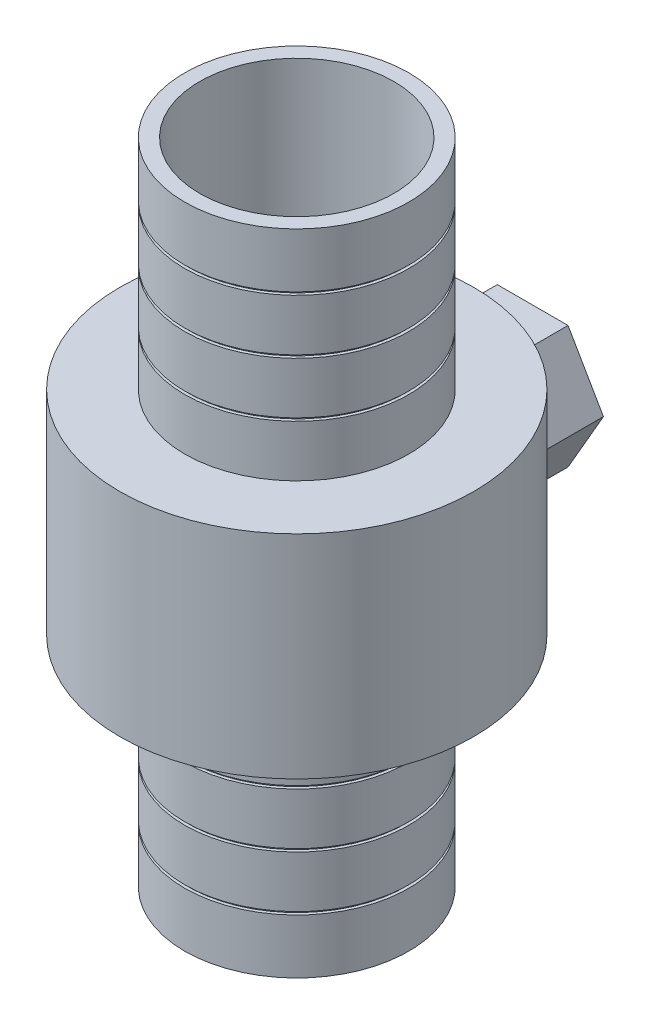
SolidWorks part; units mm, degrees
ref_plane "Front Plane" through (0, 0, 0) normal (0, 0, 1) x (1, 0, 0)
ref_plane "Top Plane" through (0, 0, 0) normal (0, 1, 0) x (1, 0, 0)
ref_plane "Right Plane" through (0, 0, 0) normal (1, 0, 0) x (0, 0, -1)
sketch "Sketch1" plane through (0, 0, 0) normal (0, 1, 0) x (1, 0, 0)
  circle A0 centre (0, 0) radius 9.5
  dimension "D1" = 19
extrude "Boss-Extrude1" add sketch "Sketch1" along normal blind 18.5
sketch "Sketch2" plane through (0, 18.5, 0) normal (0, 1, 0) x (1, 0, 0)
  circle A0 centre (0, 0) radius 15
  dimension "D1" = 30
extrude "Boss-Extrude2" add sketch "Sketch2" along normal blind 18
sketch "Sketch3" plane through (0, 36.5, 0) normal (0, 1, 0) x (1, 0, 0)
  circle A0 centre (0, 0) radius 9.5
  dimension "D1" = 19
extrude "Boss-Extrude3" add sketch "Sketch3" along normal blind 18.5
ref_plane "Plane1" through (0, 4.625, 0) normal (0, -1, 0) x (-1, 0, 0)
sketch "Sketch4" plane through (0, 4.625, 0) normal (0, -1, 0) x (-1, 0, 0)
  circle A0 centre (0, 0) radius 9.25
  circle A1 centre (0, 0) radius 9.5
  dimension "D1" = 18.5
  dimension "D2" = 19
extrude "Cut-Extrude3" cut sketch "Sketch4" against normal blind 0.25 contours A1 | A0
pattern_linear "LPattern1" count 3 spacing 4.625 along (0, 1, 0) of "Cut-Extrude3"
ref_plane "Plane2" through (0, 27.5, 0) normal (0, -1, 0) x (-1, 0, 0)
mirror "Mirror1" about plane through (0, 27.5, 0) normal (0, -1, 0) of "LPattern1", "Cut-Extrude3"
ref_plane "Plane3" through (0, 0, -15) normal (0, 0, -1) x (-1, 0, 0)
sketch "Sketch5" plane through (0, 0, -15) normal (0, 0, -1) x (-1, 0, 0)
  line L0 (-15, 36.5) -> (-15, 18.5) construction
  line L1 (-3, 22.3038) -> (3, 22.3038)
  line L2 (3, 22.3038) -> (6, 27.5)
  line L3 (6, 27.5) -> (3, 32.6962)
  line L4 (3, 32.6962) -> (-3, 32.6962)
  line L5 (-3, 32.6962) -> (-6, 27.5)
  line L6 (-6, 27.5) -> (-3, 22.3038)
  circle A0 centre (0, 27.5) radius 5.1962 construction
  point P12 (-15, 27.5)
  dimension "D1" = 12
extrude "Boss-Extrude4" add sketch "Sketch5" along normal blind 5 separate body
sketch "Sketch6" plane through (0, 55, 0) normal (0, 1, 0) x (1, 0, 0)
  circle A0 centre (0, 0) radius 8.23
  circle A1 centre (0, 0) radius 9.5 construction
  dimension "D1" = 1.27
extrude "Cut-Extrude4" cut sketch "Sketch6" against normal through all
